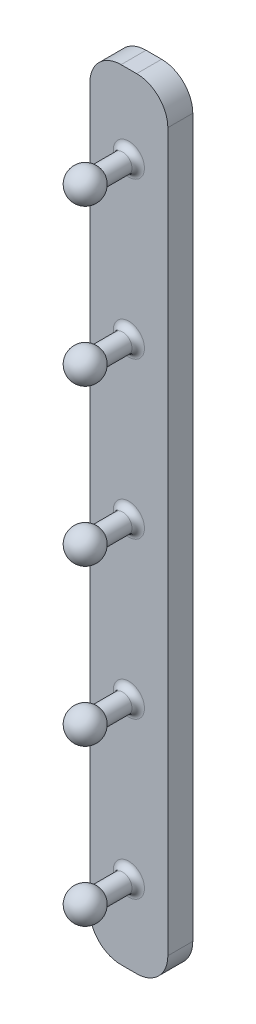
SolidWorks part; units mm, degrees
material "ABS"
ref_plane "Alzado" through (0, 0, 0) normal (1, 0, 0) x (0, 1, 0)
ref_plane "Planta" through (0, 0, 0) normal (0, 0, 1) x (0, 1, 0)
ref_plane "Vista lateral" through (0, 0, 0) normal (0, 1, 0) x (-1, 0, 0)
sketch "Croquis1" plane through (0, 0, 0) normal (0, 0, 1) x (0, 1, 0)
  line L1 (-115, 12.5) -> (115, 12.5)
  line L2 (-125, 2.5) -> (-125, -2.5)
  line L3 (-115, -12.5) -> (115, -12.5)
  line L4 (125, 2.5) -> (125, -2.5)
  line L5 (-125, 12.5) -> (125, -12.5) construction
  line L6 (-125, -12.5) -> (125, 12.5) construction
  arc A0 (-125, -2.5) -> (-115, -12.5) centre (-115, -2.5) ccw
  arc A1 (115, -12.5) -> (125, -2.5) centre (115, -2.5) ccw
  arc A2 (115, 12.5) -> (125, 2.5) centre (115, 2.5) cw
  arc A3 (-115, 12.5) -> (-125, 2.5) centre (-115, 2.5) ccw
  point P0 (0, 0)
  dimension "D3" = 10
  dimension "D1" = 25
  dimension "D2" = 250
extrude "Saliente-Extruir1" add sketch "Croquis1" along normal blind 8
sketch "Croquis2" plane through (0, 0, 8) normal (0, 0, 1) x (1, 0, 0)
  circle A0 centre (0, 0) radius 3
  dimension "D1" = 6
extrude "Saliente-Extruir2" add sketch "Croquis2" along normal blind 10
sketch "Croquis3" plane through (0, 0, 0) normal (1, 0, 0) x (0, 1, 0)
  line L1 (-3, 18) -> (0, 18)
  line L2 (3, 18) -> (-3, 18) construction
  line L3 (0, 18) -> (0, 27)
  arc A0 (-3, 18) -> (0, 27) centre (0, 22) cw
  dimension "D1" = 5
revolve "Revolución1" add sketch "Croquis3" angle 360 about L3
fillet "Redondeo1" radius 2 1 edges at (3, 0, 8)
pattern_linear "MatrizL3" count 3 spacing 50 along (0, 1, 0) count 3 spacing 50 along (0, -1, 0) of "Saliente-Extruir2", "Revolución1", "Redondeo1"
